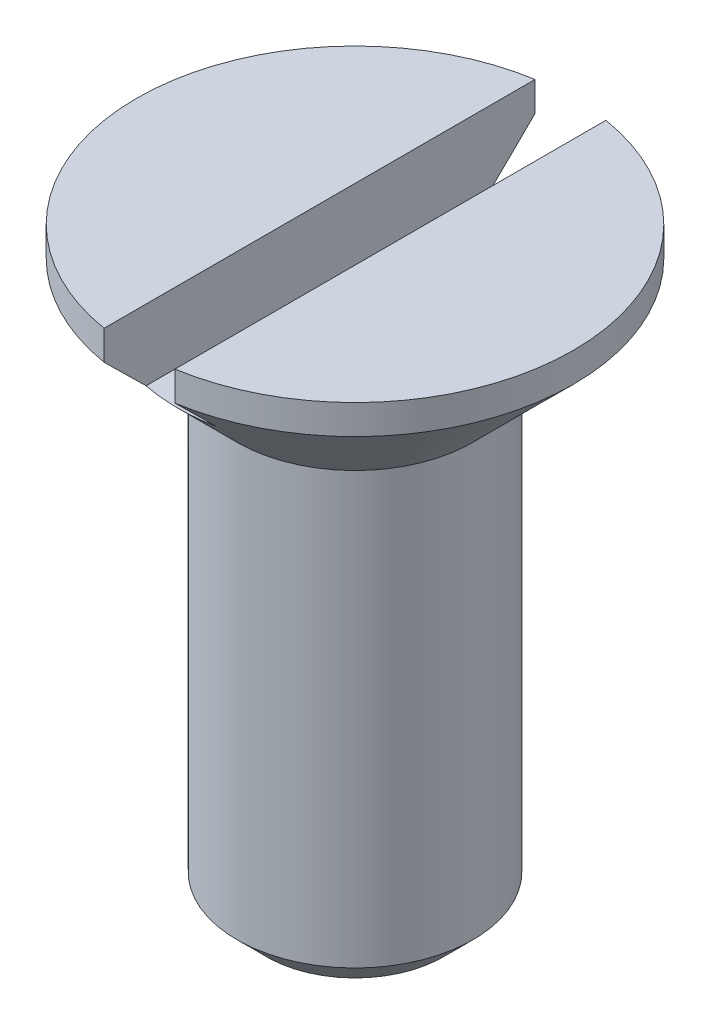
SolidWorks part; units mm, degrees
ref_plane "Спереди" through (0, 0, 0) normal (0, 0, 1) x (1, 0, 0)
ref_plane "Сверху" through (0, 0, 0) normal (0, 1, 0) x (1, 0, 0)
ref_plane "Справа" through (0, 0, 0) normal (1, 0, 0) x (0, 0, -1)
sketch "Эскиз1" plane through (0, 0, 0) normal (0, 0, 1) x (1, 0, 0)
  line L0 (0, 0) -> (-1.5, 0)
  line L1 (-1.5, 0) -> (-2, 0.5)
  line L2 (-2, 0.5) -> (-2, 7.8)
  line L3 (-2, 7.8) -> (-3.7, 9.5)
  line L4 (-3.7, 9.5) -> (-3.7, 10)
  line L5 (-3.7, 10) -> (0, 10)
  line L6 (0, 10) -> (0, 0)
  dimension "D1" = 2
  dimension "D2" = 45
  dimension "D3" = 1.5
  dimension "D4" = 10
  dimension "D5" = 45
  dimension "D6" = 2.2
  dimension "D7" = 3.7
revolve "Повернуть1" add sketch "Эскиз1" angle 360 about L6
sketch "Эскиз2" plane through (0, 0, 0) normal (0, 0, 1) x (1, 0, 0)
  line L0 (0, 0) -> (0, 10) construction
  line L1 (3.7, 10) -> (-3.7, 10) construction
  line L3 (-0.6, 10) -> (0.6, 10)
  line L4 (-0.6, 10) -> (-0.6, 8.8)
  line L5 (-0.6, 8.8) -> (0.6, 8.8)
  line L6 (0.6, 10) -> (0.6, 8.8)
  dimension "D1" = 1.2
  dimension "D2" = 1.2
extrude "Вырез-Вытянуть1" cut sketch "Эскиз2" against normal through all and the other way through all
